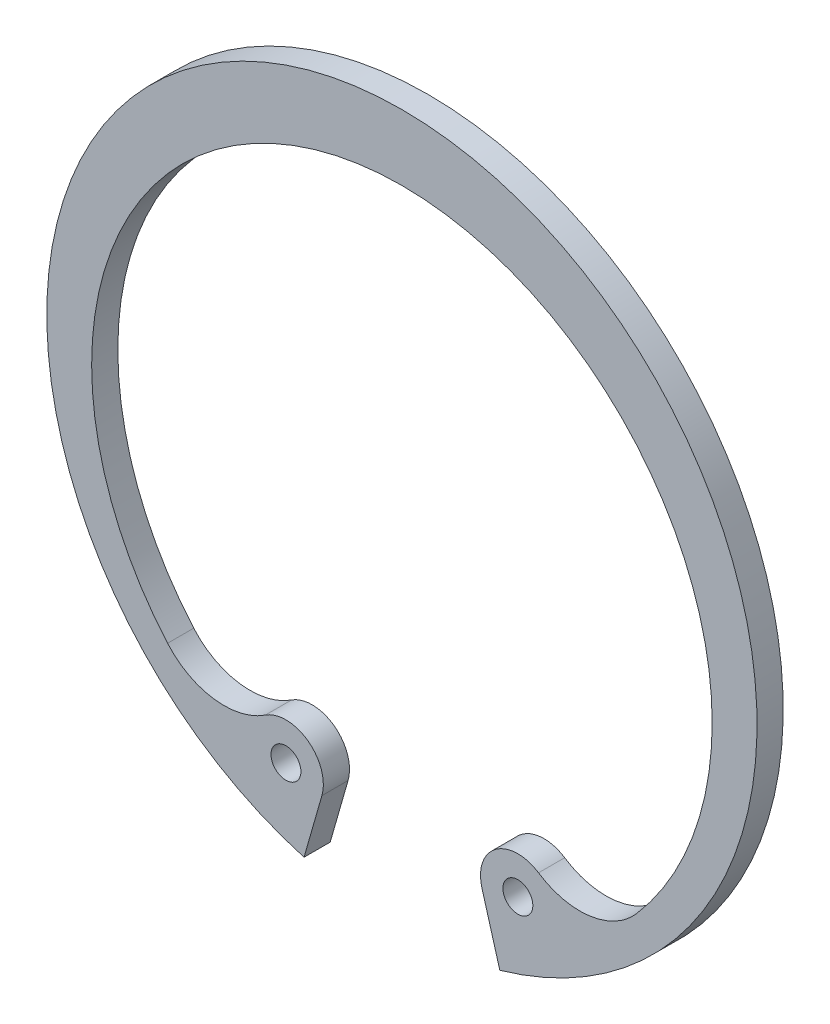
SolidWorks part; units mm, degrees
ref_plane "Front Plane" through (0, 0, 0) normal (0, 0, 1) x (1, 0, 0)
ref_plane "Top Plane" through (0, 0, 0) normal (0, 1, 0) x (1, 0, 0)
ref_plane "Right Plane" through (0, 0, 0) normal (1, 0, 0) x (0, 0, -1)
sketch "Sketch2" plane through (0, 0, 0) normal (0, 0, 1) x (1, 0, 0)
  line L0 (0, 0) -> (0, -23.75) construction
  line L1 (0, 0) -> (6.5464, -22.83)
  line L2 (0, 0) -> (-6.5464, -22.83)
  circle A0 centre (0, 0) radius 23.75
  circle A1 centre (0, -1.4) radius 20.75
  circle A6 centre (-7.7551, -17.9755) radius 2.5
  circle A7 centre (-11.896, -11.7222) radius 5
  circle A9 centre (0, -1.4) radius 15.8
  circle A10 centre (-7.7551, -17.9755) radius 1
  circle A11 centre (7.7551, -17.9755) radius 1
  circle A12 centre (7.7551, -17.9755) radius 2.5
  circle A13 centre (11.896, -11.7222) radius 5
  dimension "D1" = 47.5
  dimension "D5" = 41.5
  dimension "D2" = 10
  dimension "D6" = 5
  dimension "D7" = 31.6
  dimension "D8" = 2
  dimension "D3" = 32
  dimension "D4" = 1.4
extrude "Boss-Extrude1" add sketch "Sketch2" along normal blind 1.75 contours A7 A1 A6 | A1 A6 A10 | A1 A12 L1 A0 L2 A6 | A6 A1 L2 | A1 A12 L1 | A12 A1 A11 | A1 A13 A12 | A1 A6 | A12 A1
equation "\"D1@Sketch2\" = \"G_anneau_alesage_rouleau\""
equation "\"c_anneau\"=31.6"
equation "\"D5@Sketch2\" = \"G_anneau_alesage_rouleau\" - 6"
equation "\"e_anneau\"=1.75"
equation "\"D2@Sketch2\"=2*\"D6@Sketch2\""
equation "\"D7@Sketch2\"=\"c_anneau\""
equation "\"d_ext_rouleau\"= 90"
equation "\"epaisseur_rouleau\"=80"
equation "\"alesage-rouleau\"= 52"
equation "\"jeu_dent_rouleau\"= 2"
equation "\"profondeur_dent_rouleau\"=4"
equation "\"n_dent_roueau\"= 15"
equation "\"d_ext_roulement_rouleau\"= 42"
equation "\"d_int_roulement_rouleau\"= 20"
equation "\"B_roulement_rouleau\"= 12"
equation "\"r_roulement_rouleau\"= 0.6"
equation "\"d_bille_roulement_rouleau\"= 8"
equation "\"F_anneau_alesage_rouleau\"=1.85"
equation "\"G_anneau_alesage_rouleau\"=47.5"
equation "\"K_anneau_alesage_rouleau\"=3.75"
equation "\"d_vis_flasque_rouleau\"=5"
equation "\"l-x_vis_flasque_rouleau\"=4"
equation "\"g_anneau_arbre_rouleau\"=19"
equation "\"f_anneau_arbre_rouleau\"=1.3"
equation "\"k_anneau_arbre_rouleau\"=1.5"
equation "\"h_matrice\"= 22"
equation "\"d_matrice\"= 220"
equation "\"d_granulat\"= 8"
equation "\"zone_vide_matrice\" = 48"
equation "\"d_alesage_matrice\"=20"
equation "\"a_clavette_alesage_matrice\"=6"
equation "\"entrax_vis_rouleau\"=65"
